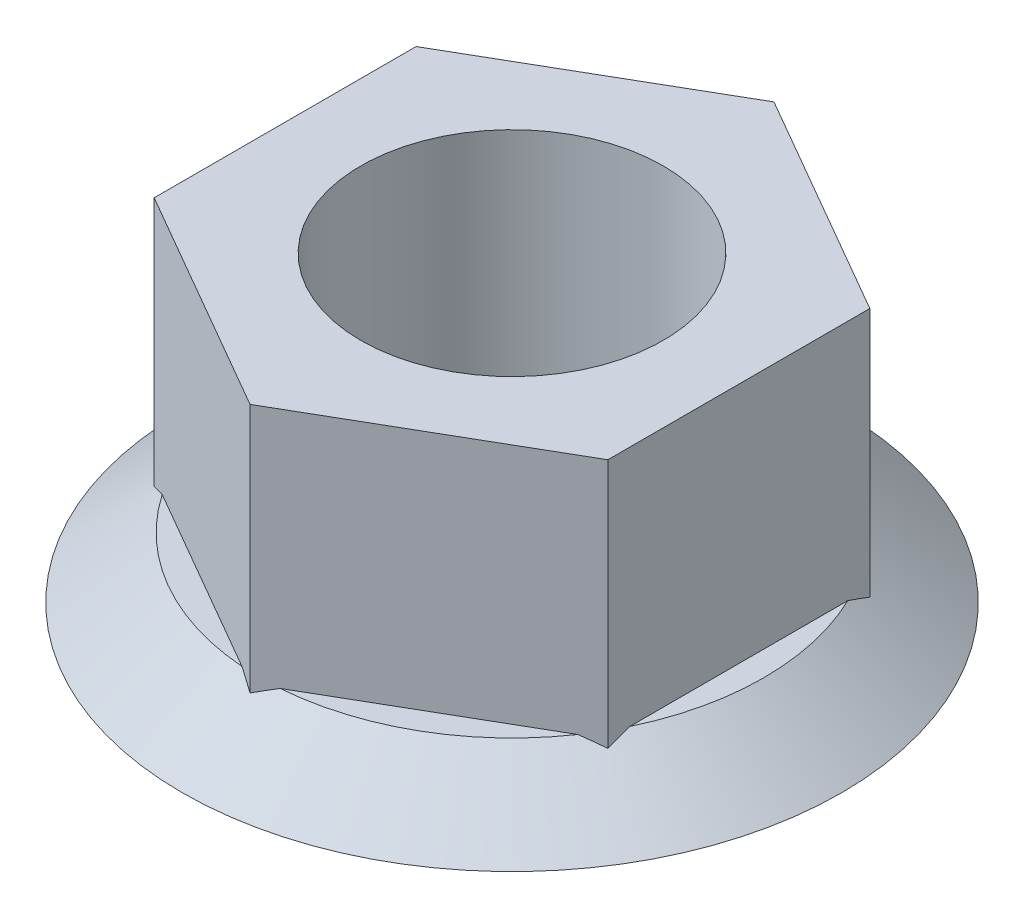
SolidWorks part; units mm, degrees
ref_plane "Płaszczyzna przednia" through (0, 0, 0) normal (0, 0, 1) x (1, 0, 0)
ref_plane "Płaszczyzna górna" through (0, 0, 0) normal (0, 1, 0) x (1, 0, 0)
ref_plane "Płaszczyzna prawa" through (0, 0, 0) normal (1, 0, 0) x (0, 0, -1)
sketch "Szkic1" plane through (0, 0, 0) normal (0, 0, 1) x (1, 0, 0)
  line L0 (5, 0) -> (5, 2)
  line L1 (5, 2) -> (8.32, 2)
  line L2 (8.32, 2) -> (10.9, 0)
  line L3 (10.9, 0) -> (5, 0)
  line L4 (0, 0) -> (0, 48.4102) construction
  dimension "D1" = 5
  dimension "D2" = 10.9
  dimension "D3" = 2
  dimension "D4" = 8.32
revolve "Obrót1" add sketch "Szkic1" angle 360 about L4
sketch "Szkic2" plane through (0, 2, 0) normal (0, 1, 0) x (1, 0, 0)
  line L1 (0, 8.6603) -> (-7.5, 4.3301)
  line L2 (-7.5, 4.3301) -> (-7.5, -4.3301)
  line L3 (-7.5, -4.3301) -> (0, -8.6603)
  line L4 (0, -8.6603) -> (7.5, -4.3301)
  line L5 (7.5, -4.3301) -> (7.5, 4.3301)
  line L6 (7.5, 4.3301) -> (0, 8.6603)
  circle A0 centre (0, 0) radius 7.5 construction
  circle A1 centre (0, 0) radius 5
  dimension "D1" = 15
extrude "Dodanie-wyciągnięcie1" add sketch "Szkic2" along normal blind 10 from surface at -2 starting at face at (0, 0, -10.9)
